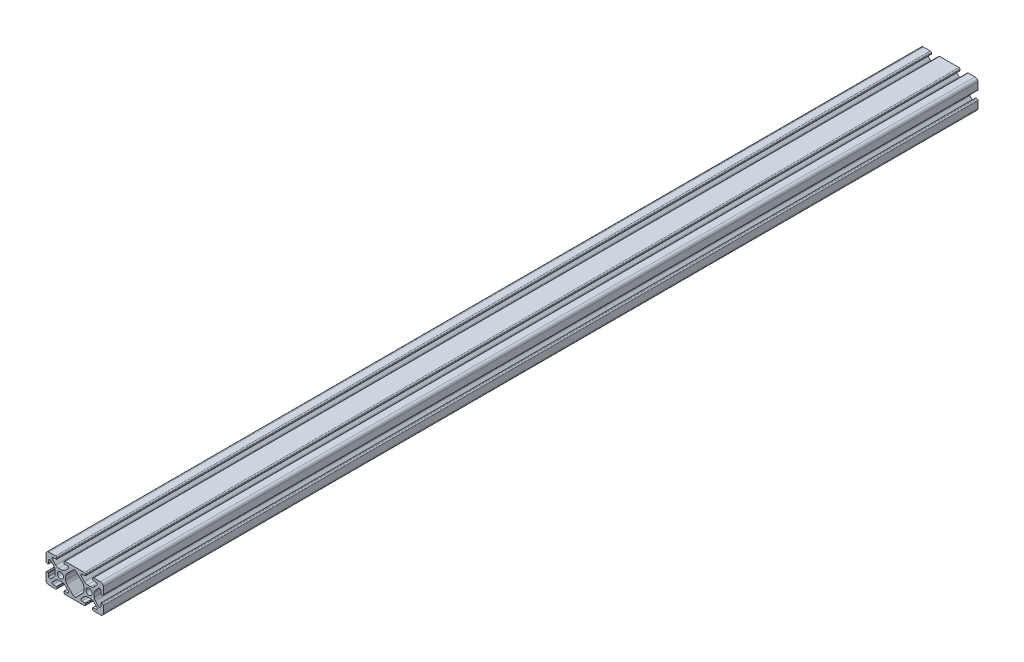
SolidWorks part; units mm, degrees
ref_plane "Front Plane" through (0, 0, 0) normal (0, 0, 1) x (1, 0, 0)
ref_plane "Top Plane" through (0, 0, 0) normal (0, 1, 0) x (1, 0, 0)
ref_plane "Right Plane" through (0, 0, 0) normal (1, 0, 0) x (0, 0, -1)
sketch "Sketch1" plane through (0, 0, 0) normal (0, 0, 1) x (1, 0, 0)
  line L2 (-19.9898, 7.9883) -> (-19.9898, 3.2893)
  line L3 (-17.9832, 9.9949) -> (-13.2842, 9.9949)
  line L4 (-12.4968, 9.2075) -> (-12.4968, 8.4963)
  line L5 (-12.8016, 8.1915) -> (-14.9098, 8.1915)
  line L6 (-15.5025, 6.7606) -> (-13.2477, 4.5058)
  line L7 (-16.7555, 5.5076) -> (-14.5007, 3.2528)
  line L8 (-18.1864, 4.9149) -> (-18.1864, 2.8067)
  line L9 (-18.4912, 2.5019) -> (-19.2024, 2.5019)
  line L11 (-11.1283, 3.6279) -> (-8.8615, 3.6279)
  line L12 (-13.6228, 1.1334) -> (-13.6228, -1.1334)
  line L13 (0, 9.9949) -> (-6.7056, 9.9949)
  line L14 (-7.493, 9.2075) -> (-7.493, 8.4963)
  line L15 (-7.1882, 8.1915) -> (-5.08, 8.1915)
  line L16 (-6.367, 1.1334) -> (-6.367, -1.1334)
  line L17 (-4.4873, 6.7606) -> (-6.7421, 4.5058)
  line L18 (-0.9396, 7.8023) -> (-5.4891, 3.2528)
  line L19 (-18.4912, -2.5019) -> (-19.2024, -2.5019)
  line L20 (-18.1864, -4.9149) -> (-18.1864, -2.8067)
  line L21 (-16.7555, -5.5076) -> (-14.5007, -3.2528)
  line L22 (-15.5025, -6.7606) -> (-13.2477, -4.5058)
  line L23 (-12.8016, -8.1915) -> (-14.9098, -8.1915)
  line L24 (-12.4968, -9.2075) -> (-12.4968, -8.4963)
  line L25 (-17.9832, -9.9949) -> (-13.2842, -9.9949)
  line L26 (-19.9898, -7.9883) -> (-19.9898, -3.2893)
  line L27 (0, -9.9949) -> (-6.7056, -9.9949)
  line L28 (-7.493, -9.2075) -> (-7.493, -8.4963)
  line L29 (-7.1882, -8.1915) -> (-5.08, -8.1915)
  line L30 (-4.4873, -6.7606) -> (-6.7421, -4.5058)
  line L31 (-0.9396, -7.8023) -> (-5.4891, -3.2528)
  line L32 (-11.1283, -3.6279) -> (-8.8615, -3.6279)
  line L34 (11.1283, -3.6279) -> (8.8615, -3.6279)
  line L35 (0.9396, -7.8023) -> (5.4891, -3.2528)
  line L36 (4.4873, -6.7606) -> (6.7421, -4.5058)
  line L37 (7.1882, -8.1915) -> (5.08, -8.1915)
  line L38 (7.493, -9.2075) -> (7.493, -8.4963)
  line L39 (0, -9.9949) -> (6.7056, -9.9949)
  line L40 (19.9898, -7.9883) -> (19.9898, -3.2893)
  line L41 (17.9832, -9.9949) -> (13.2842, -9.9949)
  line L42 (12.4968, -9.2075) -> (12.4968, -8.4963)
  line L43 (12.8016, -8.1915) -> (14.9098, -8.1915)
  line L44 (15.5025, -6.7606) -> (13.2477, -4.5058)
  line L45 (16.7555, -5.5076) -> (14.5007, -3.2528)
  line L46 (18.1864, -4.9149) -> (18.1864, -2.8067)
  line L47 (18.4912, -2.5019) -> (19.2024, -2.5019)
  line L48 (0.9396, 7.8023) -> (5.4891, 3.2528)
  line L49 (4.4873, 6.7606) -> (6.7421, 4.5058)
  line L50 (6.367, 1.1334) -> (6.367, -1.1334)
  line L51 (7.1882, 8.1915) -> (5.08, 8.1915)
  line L52 (7.493, 9.2075) -> (7.493, 8.4963)
  line L53 (0, 9.9949) -> (6.7056, 9.9949)
  line L54 (13.6228, 1.1334) -> (13.6228, -1.1334)
  line L55 (11.1283, 3.6279) -> (8.8615, 3.6279)
  line L56 (18.4912, 2.5019) -> (19.2024, 2.5019)
  line L57 (18.1864, 4.9149) -> (18.1864, 2.8067)
  line L58 (16.7555, 5.5076) -> (14.5007, 3.2528)
  line L59 (15.5025, 6.7606) -> (13.2477, 4.5058)
  line L60 (12.8016, 8.1915) -> (14.9098, 8.1915)
  line L61 (12.4968, 9.2075) -> (12.4968, 8.4963)
  line L62 (17.9832, 9.9949) -> (13.2842, 9.9949)
  line L63 (19.9898, 7.9883) -> (19.9898, 3.2893)
  circle A0 centre (-9.9949, 0) radius 2.1463
  arc A1 (-19.9898, 7.9883) -> (-17.9832, 9.9949) centre (-17.9832, 7.9883) cw
  arc A2 (-16.7555, 5.5076) -> (-18.1864, 4.9149) centre (-17.3482, 4.9149) ccw
  arc A3 (-14.9098, 8.1915) -> (-15.5025, 6.7606) centre (-14.9098, 7.3533) ccw
  arc A4 (-13.2842, 9.9949) -> (-12.4968, 9.2075) centre (-13.2842, 9.2075) cw
  arc A5 (-19.9898, 3.2893) -> (-19.2024, 2.5019) centre (-19.2024, 3.2893) ccw
  arc A6 (-18.1864, 2.8067) -> (-18.4912, 2.5019) centre (-18.4912, 2.8067) cw
  arc A7 (-12.4968, 8.4963) -> (-12.8016, 8.1915) centre (-12.8016, 8.4963) cw
  arc A8 (-11.1283, 3.6279) -> (-13.2477, 4.5058) centre (-11.1283, 6.6251) cw
  arc A9 (-13.6228, 1.1334) -> (-14.5007, 3.2528) centre (-16.62, 1.1334) ccw
  arc A10 (0.9396, 7.8023) -> (-0.9396, 7.8023) centre (0, 6.8627) ccw
  arc A11 (-0.9396, -7.8023) -> (0.9396, -7.8023) centre (0, -6.8627) ccw
  arc A12 (-6.7056, 9.9949) -> (-7.493, 9.2075) centre (-6.7056, 9.2075) ccw
  arc A13 (-7.493, 8.4963) -> (-7.1882, 8.1915) centre (-7.1882, 8.4963) ccw
  arc A14 (-8.8615, 3.6279) -> (-6.7421, 4.5058) centre (-8.8615, 6.6251) ccw
  arc A15 (-6.367, 1.1334) -> (-5.4891, 3.2528) centre (-3.3698, 1.1334) cw
  arc A16 (-5.08, 8.1915) -> (-4.4873, 6.7606) centre (-5.08, 7.3533) cw
  arc A17 (-13.6228, -1.1334) -> (-14.5007, -3.2528) centre (-16.62, -1.1334) cw
  arc A18 (-11.1283, -3.6279) -> (-13.2477, -4.5058) centre (-11.1283, -6.6251) ccw
  arc A19 (-12.4968, -8.4963) -> (-12.8016, -8.1915) centre (-12.8016, -8.4963) ccw
  arc A20 (-18.1864, -2.8067) -> (-18.4912, -2.5019) centre (-18.4912, -2.8067) ccw
  arc A21 (-19.9898, -3.2893) -> (-19.2024, -2.5019) centre (-19.2024, -3.2893) cw
  arc A22 (-13.2842, -9.9949) -> (-12.4968, -9.2075) centre (-13.2842, -9.2075) ccw
  arc A23 (-14.9098, -8.1915) -> (-15.5025, -6.7606) centre (-14.9098, -7.3533) cw
  arc A24 (-16.7555, -5.5076) -> (-18.1864, -4.9149) centre (-17.3482, -4.9149) cw
  arc A25 (-19.9898, -7.9883) -> (-17.9832, -9.9949) centre (-17.9832, -7.9883) ccw
  arc A26 (-5.08, -8.1915) -> (-4.4873, -6.7606) centre (-5.08, -7.3533) ccw
  arc A27 (-6.7056, -9.9949) -> (-7.493, -9.2075) centre (-6.7056, -9.2075) cw
  arc A28 (-7.493, -8.4963) -> (-7.1882, -8.1915) centre (-7.1882, -8.4963) cw
  arc A29 (-8.8615, -3.6279) -> (-6.7421, -4.5058) centre (-8.8615, -6.6251) cw
  arc A30 (-6.367, -1.1334) -> (-5.4891, -3.2528) centre (-3.3698, -1.1334) ccw
  arc A31 (6.367, -1.1334) -> (5.4891, -3.2528) centre (3.3698, -1.1334) cw
  arc A32 (8.8615, -3.6279) -> (6.7421, -4.5058) centre (8.8615, -6.6251) ccw
  arc A33 (7.493, -8.4963) -> (7.1882, -8.1915) centre (7.1882, -8.4963) ccw
  arc A34 (6.7056, -9.9949) -> (7.493, -9.2075) centre (6.7056, -9.2075) ccw
  arc A35 (5.08, -8.1915) -> (4.4873, -6.7606) centre (5.08, -7.3533) cw
  arc A36 (19.9898, -7.9883) -> (17.9832, -9.9949) centre (17.9832, -7.9883) cw
  arc A37 (16.7555, -5.5076) -> (18.1864, -4.9149) centre (17.3482, -4.9149) ccw
  arc A38 (14.9098, -8.1915) -> (15.5025, -6.7606) centre (14.9098, -7.3533) ccw
  arc A39 (13.2842, -9.9949) -> (12.4968, -9.2075) centre (13.2842, -9.2075) cw
  arc A40 (19.9898, -3.2893) -> (19.2024, -2.5019) centre (19.2024, -3.2893) ccw
  arc A41 (18.1864, -2.8067) -> (18.4912, -2.5019) centre (18.4912, -2.8067) cw
  arc A42 (12.4968, -8.4963) -> (12.8016, -8.1915) centre (12.8016, -8.4963) cw
  arc A43 (11.1283, -3.6279) -> (13.2477, -4.5058) centre (11.1283, -6.6251) cw
  arc A44 (13.6228, -1.1334) -> (14.5007, -3.2528) centre (16.62, -1.1334) ccw
  arc A45 (5.08, 8.1915) -> (4.4873, 6.7606) centre (5.08, 7.3533) ccw
  arc A46 (6.367, 1.1334) -> (5.4891, 3.2528) centre (3.3698, 1.1334) ccw
  arc A47 (8.8615, 3.6279) -> (6.7421, 4.5058) centre (8.8615, 6.6251) cw
  arc A48 (7.493, 8.4963) -> (7.1882, 8.1915) centre (7.1882, 8.4963) cw
  arc A49 (6.7056, 9.9949) -> (7.493, 9.2075) centre (6.7056, 9.2075) cw
  arc A50 (13.6228, 1.1334) -> (14.5007, 3.2528) centre (16.62, 1.1334) cw
  arc A51 (11.1283, 3.6279) -> (13.2477, 4.5058) centre (11.1283, 6.6251) ccw
  arc A52 (12.4968, 8.4963) -> (12.8016, 8.1915) centre (12.8016, 8.4963) ccw
  arc A53 (18.1864, 2.8067) -> (18.4912, 2.5019) centre (18.4912, 2.8067) ccw
  arc A54 (19.9898, 3.2893) -> (19.2024, 2.5019) centre (19.2024, 3.2893) cw
  arc A55 (13.2842, 9.9949) -> (12.4968, 9.2075) centre (13.2842, 9.2075) ccw
  arc A56 (14.9098, 8.1915) -> (15.5025, 6.7606) centre (14.9098, 7.3533) cw
  arc A57 (16.7555, 5.5076) -> (18.1864, 4.9149) centre (17.3482, 4.9149) cw
  arc A58 (19.9898, 7.9883) -> (17.9832, 9.9949) centre (17.9832, 7.9883) ccw
  circle A59 centre (9.9949, 0) radius 2.1463
  point P186 (9.9949, 3.6279)
extrude "Boss-Extrude1" add sketch "Sketch1" along normal mid plane 609.6
